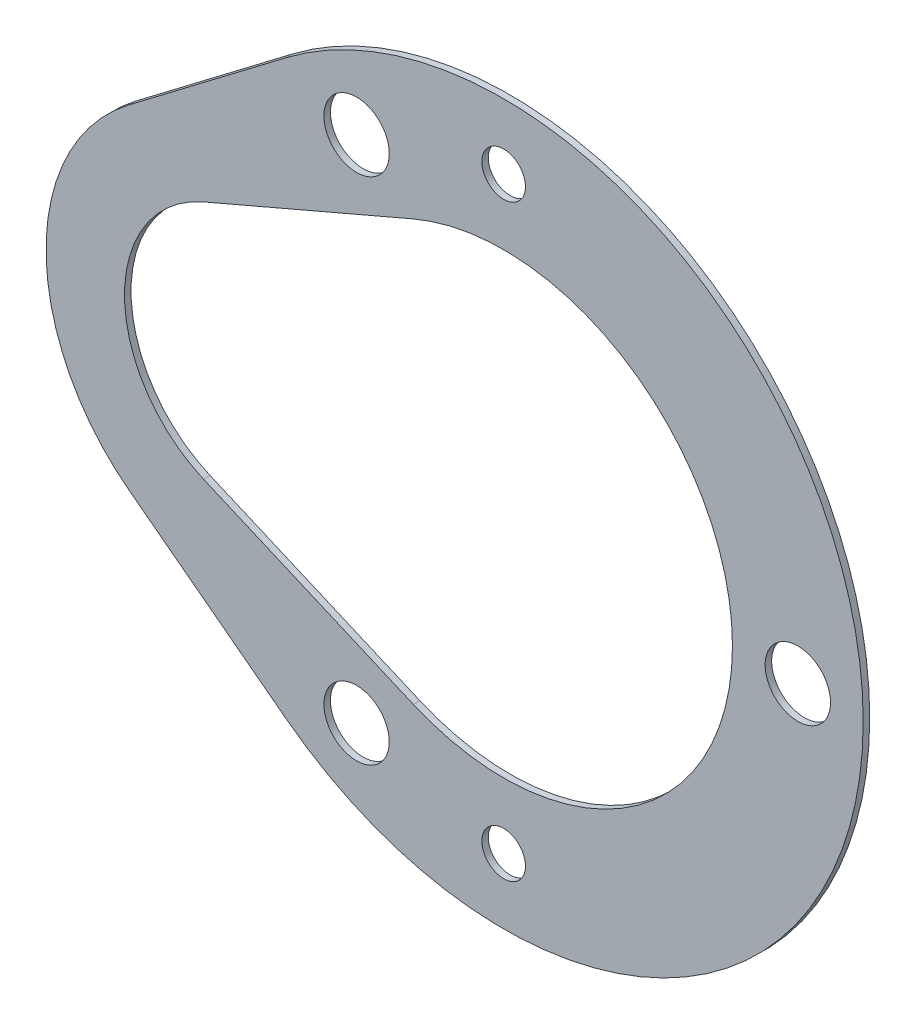
SolidWorks part; units mm, degrees
ref_plane "Спереди" through (0, 0, 0) normal (0, 0, 1) x (1, 0, 0)
ref_plane "Сверху" through (0, 0, 0) normal (0, 1, 0) x (1, 0, 0)
ref_plane "Справа" through (0, 0, 0) normal (1, 0, 0) x (0, 0, -1)
other "Configuration Table"
sketch "Эскиз1" plane through (0, 0, 0) normal (0, 0, 1) x (1, 0, 0)
  line L0 (-57.3684, 25.4728) -> (-33.2895, 43.7814)
  line L1 (-57.3684, -25.4728) -> (-33.2895, -43.7814)
  line L2 (-45.8947, 18.3759) -> (-13.8158, 32.1578)
  line L3 (-45.8947, -18.3759) -> (-13.8158, -32.1578)
  arc A0 (-57.3684, 25.4728) -> (-57.3684, -25.4728) centre (-38, 0) ccw
  arc A1 (-33.2895, -43.7814) -> (-33.2895, 43.7814) centre (0, 0) ccw
  circle A5 centre (-22.5, 38.9711) radius 5
  circle A6 centre (45, 0) radius 5
  circle A7 centre (-22.5, -38.9711) radius 5
  arc A12 (-13.8158, -32.1578) -> (-13.8158, 32.1578) centre (0, 0) ccw
  arc A13 (-45.8947, 18.3759) -> (-45.8947, -18.3759) centre (-38, 0) ccw
  dimension "D1" = 10
  dimension "D2" = 38
  dimension "D3" = 40
  dimension "D4" = 70
  dimension "D5" = 32
  dimension "D6" = 55
  dimension "D7" = 45
  dimension "D8" = 22.5
  dimension "D9" = 38.9711
  dimension "D10" = 38.9711
extrude "Бобышка-Вытянуть1" add sketch "Эскиз1" along normal blind 1
ref_plane "Плоскость3" through (0, 45, 0) normal (0, 1, 0) x (1, 0, 0)
ref_plane "Плоскость1" through (0, 0, -24) normal (0, 0, -1) x (-1, 0, 0)
ref_plane "Плоскость2" through (0, 0, 21) normal (0, 0, 1) x (1, 0, 0)
sketch "Эскиз2" plane through (0, 0, -24) normal (0, 0, -1) x (-1, 0, 0)
  circle A0 centre (0, 0) radius 45 construction
  circle A1 centre (0, 45) radius 3.75
  circle A2 centre (0, -45) radius 3.75
  dimension "D1" = 7.5
  dimension "D2" = 7.5
  dimension "D3" = 90
sketch "Эскиз3" plane through (0, 0, 21) normal (0, 0, 1) x (1, 0, 0)
  circle A0 centre (0, 45) radius 3
  circle A1 centre (0, -45) radius 3
  dimension "D1" = 6
  dimension "D2" = 6
loft "Вырез-По сечениям1" cut section "Эскиз3" section "Эскиз2"
mirror "Зеркальное отражение1" about plane through (0, 0, 0) normal (0, 1, 0) of "Вырез-По сечениям1"
